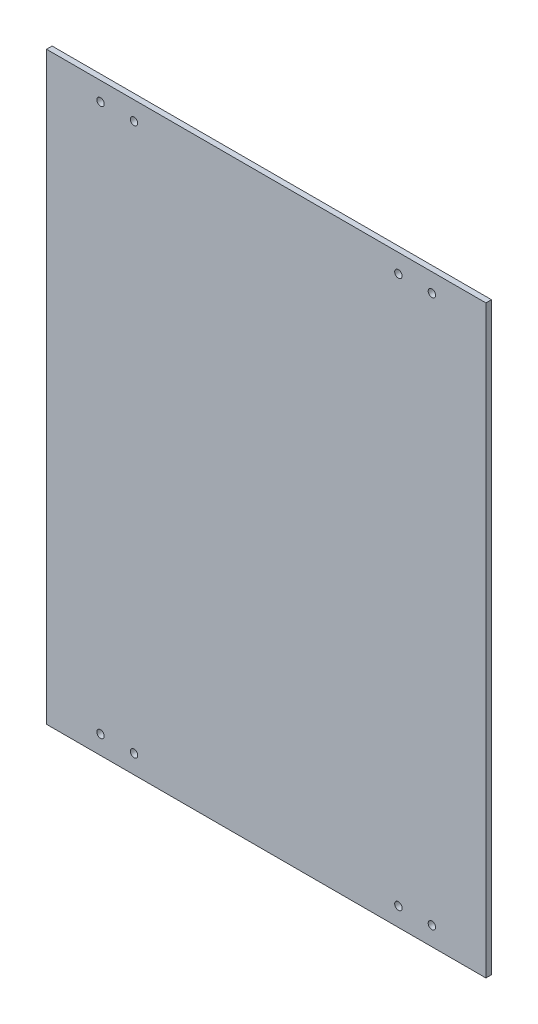
SolidWorks part; units mm, degrees
ref_plane "Plan de face" through (0, 0, 0) normal (0, 0, 1) x (1, 0, 0)
ref_plane "Plan de dessus" through (0, 0, 0) normal (0, 1, 0) x (1, 0, 0)
ref_plane "Plan de droite" through (0, 0, 0) normal (1, 0, 0) x (0, 0, -1)
sketch "Esquisse1" plane through (0, 0, 0) normal (0, 0, 1) x (1, 0, 0)
  line L0 (0, 0) -> (118, 0) construction
  line L1 (0, 0) -> (-118, 0) construction
  line L2 (-118, 0) -> (-118, 154) construction
  line L3 (-118, 154) -> (118, 154)
  line L4 (118, 154) -> (118, -160)
  line L5 (118, -160) -> (-118, -160)
  line L7 (-118, 154) -> (-118, -160)
  dimension "D1" = 160
  dimension "D2" = 118
  dimension "D4" = 314
extrude "Boss.-Extru.1" add sketch "Esquisse1" along normal blind 3
sketch "Esquisse3" plane through (0, 0, 3) normal (0, 0, 1) x (1, 0, 0)
  line L0 (0, -160) -> (-80, -160) construction
  line L1 (-118, -160) -> (118, -160) construction
  line L2 (-80, -160) -> (-80, -150) construction
  line L3 (-80, -150) -> (-71, -150) construction
  line L4 (-80, -150) -> (-89, -150) construction
  line L5 (-118, -3) -> (118, -3) construction
  line L6 (-118, 154) -> (-118, -160) construction
  line L7 (118, -160) -> (118, 154) construction
  line L8 (-80, 144) -> (-89, 144) construction
  line L9 (-80, 144) -> (-71, 144) construction
  line L10 (-80, 154) -> (-80, 144) construction
  line L11 (0, 154) -> (-80, 154) construction
  line L12 (0, -55) -> (0, 55) construction
  line L13 (80, 154) -> (80, 144) construction
  line L14 (80, 144) -> (71, 144) construction
  line L15 (80, 144) -> (89, 144) construction
  circle A0 centre (-71, -150) radius 2
  circle A1 centre (-89, -150) radius 2
  circle A2 centre (-89, 144) radius 2
  circle A3 centre (-71, 144) radius 2
  circle A4 centre (71, 144) radius 2
  circle A5 centre (89, 144) radius 2
  dimension "D3" = 9
  dimension "D1" = 10
  dimension "D2" = 9
extrude "Enlèv. mat.-Extru.1" cut sketch "Esquisse3" against normal up to next
mirror "Symétrie1" about plane through (0, 0, 0) normal (1, 0, 0) of "Enlèv. mat.-Extru.1"
